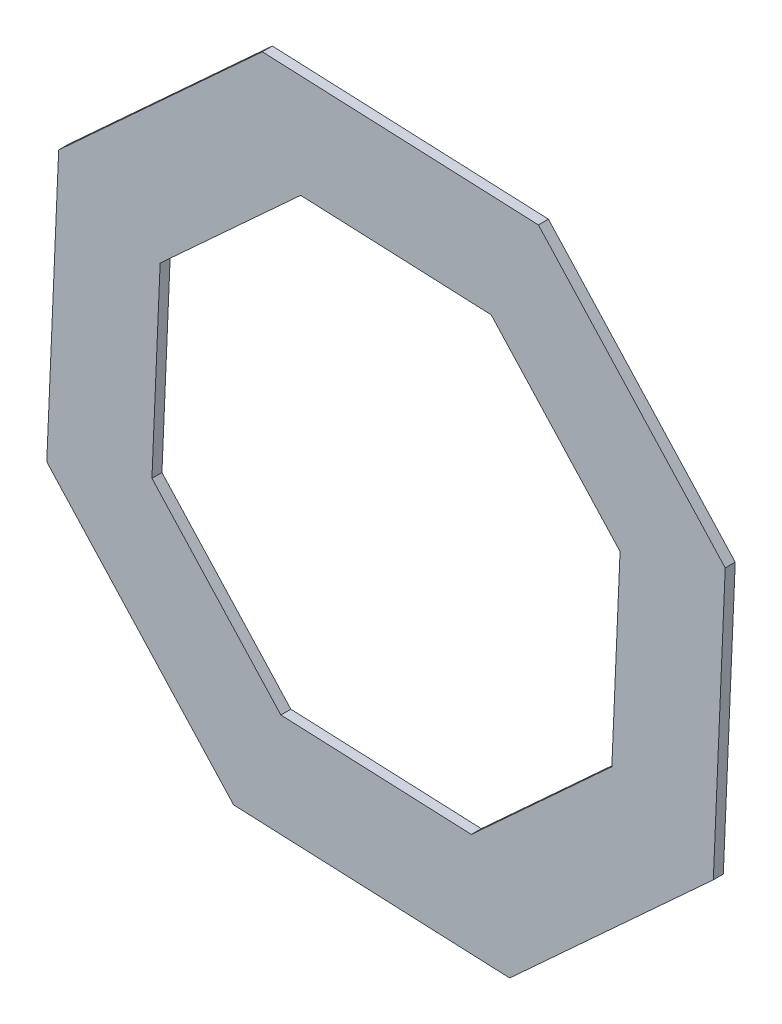
SolidWorks part; units mm, degrees
ref_plane "Alzado" through (0, 0, 0) normal (0, 0, 1) x (1, 0, 0)
ref_plane "Planta" through (0, 0, 0) normal (0, 1, 0) x (1, 0, 0)
ref_plane "Vista lateral" through (0, 0, 0) normal (1, 0, 0) x (0, 0, -1)
sketch "Croquis1" plane through (0, 0, 0) normal (0, 0, 1) x (1, 0, 0)
  line L0 (-45.692, -98.1222) -> (37.0737, -101.692)
  line L1 (98.1222, -45.692) -> (101.692, 37.0737)
  line L2 (101.692, 37.0737) -> (45.692, 98.1222)
  line L3 (45.692, 98.1222) -> (-37.0737, 101.692)
  line L4 (-37.0737, 101.692) -> (-98.1222, 45.692)
  line L5 (-98.1222, 45.692) -> (-101.692, -37.0737)
  line L6 (-101.692, -37.0737) -> (-45.692, -98.1222)
  line L7 (37.0737, -101.692) -> (98.1222, -45.692)
  circle A0 centre (0, 0) radius 100 construction
  dimension "D1" = 200
  dimension "D2" = 56
extrude "Saliente-Extruir1" add sketch "Croquis1" along normal blind 3 contours L4 L5 L6 L0 L7 L1 L2 L3
sketch "Croquis2" plane through (0, 0, 0) normal (0, 0, -1) x (-1, 0, 0)
  line L1 (-67.7043, -31.5275) -> (-25.5809, -70.1675)
  line L2 (-25.5809, -70.1675) -> (31.5275, -67.7043)
  line L3 (31.5275, -67.7043) -> (70.1675, -25.5809)
  line L4 (70.1675, -25.5809) -> (67.7043, 31.5275)
  line L5 (67.7043, 31.5275) -> (25.5809, 70.1675)
  line L6 (25.5809, 70.1675) -> (-31.5275, 67.7043)
  line L7 (-31.5275, 67.7043) -> (-70.1675, 25.5809)
  line L8 (-70.1675, 25.5809) -> (-67.7043, -31.5275)
  line L10 (-101.692, 37.0737) -> (-45.692, 98.1222) construction
  circle A0 centre (0, 0) radius 69 construction
  dimension "D1" = 138
  dimension "D2" = 0
extrude "Cortar-Extruir1" cut sketch "Croquis2" against normal blind 3
